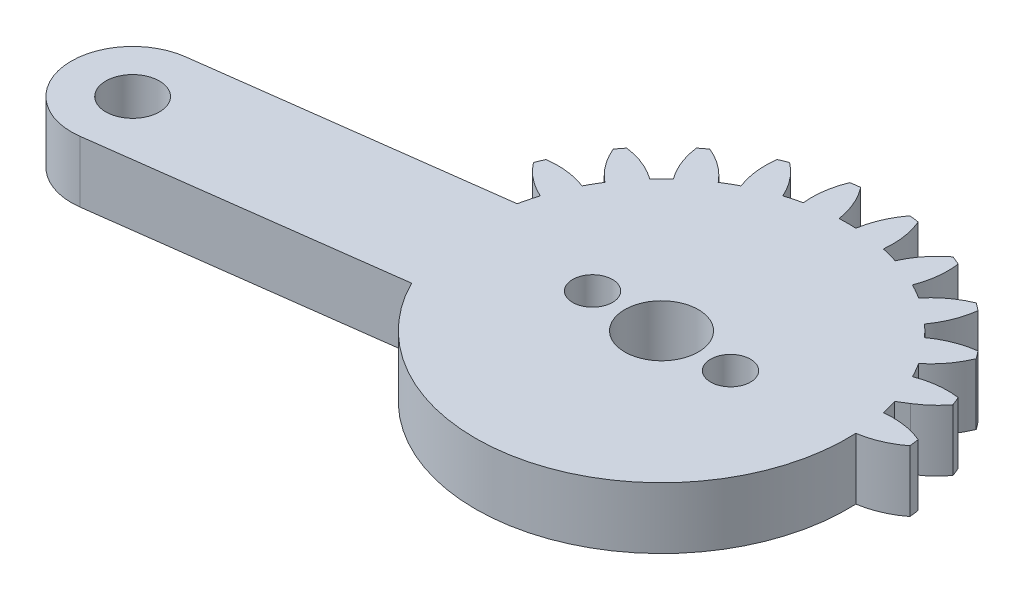
SolidWorks part; units mm, degrees
ref_plane "Front Plane" through (0, 0, 0) normal (0, 0, 1) x (1, 0, 0)
ref_plane "Top Plane" through (0, 0, 0) normal (0, 1, 0) x (1, 0, 0)
ref_plane "Right Plane" through (0, 0, 0) normal (1, 0, 0) x (0, 0, -1)
sketch "Sketch1" plane through (0, 0, 0) normal (0, 1, 0) x (1, 0, 0)
  line L0 (20.6437, 4) -> (2.0816, 4)
  line L1 (2.0816, -4) -> (20.6437, -4)
  arc A0 (2.0816, 4) -> (3.5217, 5.3071) centre (-0.7683, 8.5867) ccw
  arc A1 (3.5217, 5.3071) -> (3.2829, 5.8838) centre (-10.1063, 0) ccw
  arc A2 (3.2829, 5.8838) -> (0.6271, 5.5703) centre (2.5684, 0.5313) ccw
  arc A3 (0.6271, 5.5703) -> (0.0844, 6.5103) centre (-10.1063, 0) ccw
  arc A4 (0.0844, 6.5103) -> (1.6838, 8.6535) centre (-3.3089, 10.711) ccw
  arc A5 (1.6838, 8.6535) -> (1.3038, 9.1487) centre (-10.1063, 0) ccw
  arc A6 (1.3038, 9.1487) -> (-1.1803, 8.1585) centre (1.999, 3.7936) ccw
  arc A7 (-1.1803, 8.1585) -> (-1.9479, 8.926) centre (-10.1063, 0) ccw
  arc A8 (-1.9479, 8.926) -> (-0.9576, 11.4102) centre (-6.3127, 12.1053) ccw
  arc A9 (-0.9576, 11.4102) -> (-1.4528, 11.7901) centre (-10.1063, 0) ccw
  arc A10 (-1.4528, 11.7901) -> (-3.596, 10.1907) centre (0.6046, 6.7975) ccw
  arc A11 (-3.596, 10.1907) -> (-4.5361, 10.7334) centre (-10.1063, 0) ccw
  arc A12 (-4.5361, 10.7334) -> (-4.2225, 13.3892) centre (-9.5751, 12.6747) ccw
  arc A13 (-4.2225, 13.3892) -> (-4.7992, 13.6281) centre (-10.1063, 0) ccw
  arc A14 (-4.7992, 13.6281) -> (-6.4554, 11.5285) centre (-1.5196, 9.3381) ccw
  arc A15 (-6.4554, 11.5285) -> (-7.5039, 11.8094) centre (-10.1063, 0) ccw
  arc A16 (-7.5039, 11.8094) -> (-7.8884, 14.4558) centre (-12.8736, 12.3803) ccw
  arc A17 (-7.8884, 14.4558) -> (-8.5072, 14.5373) centre (-10.1063, 0) ccw
  arc A18 (-8.5072, 14.5373) -> (-9.5636, 12.0806) centre (-4.2291, 11.2423) ccw
  arc A19 (-9.5636, 12.0806) -> (-10.6491, 12.0806) centre (-10.1063, 0) ccw
  arc A20 (-10.6491, 12.0806) -> (-11.7054, 14.5373) centre (-15.9836, 11.2423) ccw
  arc A21 (-11.7054, 14.5373) -> (-12.3243, 14.4558) centre (-10.1063, 0) ccw
  arc A22 (-12.3243, 14.4558) -> (-12.7088, 11.8094) centre (-7.3391, 12.3803) ccw
  arc A23 (-12.7088, 11.8094) -> (-13.7573, 11.5285) centre (-10.1063, 0) ccw
  arc A24 (-13.7573, 11.5285) -> (-15.4135, 13.6281) centre (-18.6931, 9.3381) ccw
  arc A25 (-15.4135, 13.6281) -> (-15.9901, 13.3892) centre (-10.1063, 0) ccw
  arc A26 (-15.9901, 13.3892) -> (-15.6766, 10.7334) centre (-10.6376, 12.6747) ccw
  arc A27 (-15.6766, 10.7334) -> (-16.6166, 10.1907) centre (-10.1063, 0) ccw
  arc A28 (-16.6166, 10.1907) -> (-18.7599, 11.7901) centre (-20.8173, 6.7975) ccw
  arc A29 (-18.7599, 11.7901) -> (-19.255, 11.4102) centre (-10.1063, 0) ccw
  arc A30 (-19.255, 11.4102) -> (-18.2648, 8.926) centre (-13.9, 12.1053) ccw
  arc A31 (-18.2648, 8.926) -> (-19.0324, 8.1585) centre (-10.1063, 0) ccw
  arc A32 (-19.0324, 8.1585) -> (-21.5165, 9.1487) centre (-22.2117, 3.7936) ccw
  arc A33 (-21.5165, 9.1487) -> (-21.8965, 8.6535) centre (-10.1063, 0) ccw
  arc A34 (-21.8965, 8.6535) -> (-20.2971, 6.5103) centre (-16.9038, 10.711) ccw
  arc A35 (-20.2971, 6.5103) -> (-20.8398, 5.5703) centre (-10.1063, 0) ccw
  arc A36 (-20.8398, 5.5703) -> (-23.4956, 5.8838) centre (-22.7811, 0.5313) ccw
  arc A37 (-23.4956, 5.8838) -> (-23.7344, 5.3071) centre (-10.1063, 0) ccw
  arc A38 (-23.7344, 5.3071) -> (-21.6348, 3.6509) centre (-19.4444, 8.5867) ccw
  arc A39 (-21.6348, 3.6509) -> (-21.9157, 2.6025) centre (-10.1063, 0) ccw
  arc A40 (-21.9157, 2.6025) -> (-24.5622, 2.2179) centre (-22.4867, -2.7673) ccw
  arc A41 (-24.5622, 2.2179) -> (-24.6437, 1.5991) centre (-10.1063, 0) ccw
  arc A42 (-24.6437, 1.5991) -> (-22.1869, 0.5427) centre (-21.3486, 5.8773) ccw
  arc A43 (-22.1869, 0.5427) -> (-22.1869, -0.5427) centre (-10.1063, 0) ccw
  arc A44 (-22.1869, -0.5427) -> (-24.6437, -1.5991) centre (-21.3486, -5.8773) ccw
  arc A45 (-24.6437, -1.5991) -> (-24.5622, -2.2179) centre (-10.1063, 0) ccw
  arc A46 (-24.5622, -2.2179) -> (-21.9157, -2.6025) centre (-22.4867, 2.7673) ccw
  arc A47 (-21.9157, -2.6025) -> (-21.6348, -3.6509) centre (-10.1063, 0) ccw
  arc A48 (-21.6348, -3.6509) -> (-23.7344, -5.3071) centre (-19.4444, -8.5867) ccw
  arc A49 (-23.7344, -5.3071) -> (-23.4956, -5.8838) centre (-10.1063, 0) ccw
  arc A50 (-23.4956, -5.8838) -> (-20.8398, -5.5703) centre (-22.7811, -0.5313) ccw
  arc A51 (-20.8398, -5.5703) -> (-20.2971, -6.5103) centre (-10.1063, 0) ccw
  arc A52 (-20.2971, -6.5103) -> (-21.8965, -8.6535) centre (-16.9038, -10.711) ccw
  arc A53 (-21.8965, -8.6535) -> (-21.5165, -9.1487) centre (-10.1063, 0) ccw
  arc A54 (-21.5165, -9.1487) -> (-19.0324, -8.1585) centre (-22.2117, -3.7936) ccw
  arc A55 (-19.0324, -8.1585) -> (-18.2648, -8.926) centre (-10.1063, 0) ccw
  arc A56 (-18.2648, -8.926) -> (-19.255, -11.4102) centre (-13.9, -12.1053) ccw
  arc A57 (-19.255, -11.4102) -> (-18.7599, -11.7901) centre (-10.1063, 0) ccw
  arc A58 (-18.7599, -11.7901) -> (-16.6166, -10.1907) centre (-20.8173, -6.7975) ccw
  arc A59 (-16.6166, -10.1907) -> (-15.6766, -10.7334) centre (-10.1063, 0) ccw
  arc A60 (-15.6766, -10.7334) -> (-15.9901, -13.3892) centre (-10.6376, -12.6747) ccw
  arc A61 (-15.9901, -13.3892) -> (-15.4135, -13.6281) centre (-10.1063, 0) ccw
  arc A62 (-15.4135, -13.6281) -> (-13.7573, -11.5285) centre (-18.6931, -9.3381) ccw
  arc A63 (-13.7573, -11.5285) -> (-12.7088, -11.8094) centre (-10.1063, 0) ccw
  arc A64 (-12.7088, -11.8094) -> (-12.3243, -14.4558) centre (-7.3391, -12.3803) ccw
  arc A65 (-12.3243, -14.4558) -> (-11.7054, -14.5373) centre (-10.1063, 0) ccw
  arc A66 (-11.7054, -14.5373) -> (-10.6491, -12.0806) centre (-15.9836, -11.2423) ccw
  arc A67 (-10.6491, -12.0806) -> (-9.5636, -12.0806) centre (-10.1063, 0) ccw
  arc A68 (-9.5636, -12.0806) -> (-8.5072, -14.5373) centre (-4.2291, -11.2423) ccw
  arc A69 (-8.5072, -14.5373) -> (-7.8884, -14.4558) centre (-10.1063, 0) ccw
  arc A70 (-7.8884, -14.4558) -> (-7.5039, -11.8094) centre (-12.8736, -12.3803) ccw
  arc A71 (-7.5039, -11.8094) -> (-6.4554, -11.5285) centre (-10.1063, 0) ccw
  arc A72 (-6.4554, -11.5285) -> (-4.7992, -13.6281) centre (-1.5196, -9.3381) ccw
  arc A73 (-4.7992, -13.6281) -> (-4.2225, -13.3892) centre (-10.1063, 0) ccw
  arc A74 (-4.2225, -13.3892) -> (-4.5361, -10.7334) centre (-9.5751, -12.6747) ccw
  arc A75 (-4.5361, -10.7334) -> (-3.596, -10.1907) centre (-10.1063, 0) ccw
  arc A76 (-3.596, -10.1907) -> (-1.4528, -11.7901) centre (0.6046, -6.7975) ccw
  arc A77 (-1.4528, -11.7901) -> (-0.9576, -11.4102) centre (-10.1063, 0) ccw
  arc A78 (-0.9576, -11.4102) -> (-1.9479, -8.926) centre (-6.3127, -12.1053) ccw
  arc A79 (-1.9479, -8.926) -> (-1.1803, -8.1585) centre (-10.1063, 0) ccw
  arc A80 (-1.1803, -8.1585) -> (1.3038, -9.1487) centre (1.999, -3.7936) ccw
  arc A81 (1.3038, -9.1487) -> (1.6838, -8.6535) centre (-10.1063, 0) ccw
  arc A82 (1.6838, -8.6535) -> (0.0844, -6.5103) centre (-3.3089, -10.711) ccw
  arc A83 (0.0844, -6.5103) -> (0.6271, -5.5703) centre (-10.1063, 0) ccw
  arc A84 (0.6271, -5.5703) -> (3.2829, -5.8838) centre (2.5684, -0.5313) ccw
  arc A85 (3.2829, -5.8838) -> (3.5217, -5.3071) centre (-10.1063, 0) ccw
  arc A86 (3.5217, -5.3071) -> (2.0816, -4) centre (-0.7683, -8.5867) ccw
  arc A87 (20.6437, -4) -> (20.6437, 4) centre (20.6437, 0) ccw
  circle A88 centre (-10.1063, 0) radius 1.5
  circle A89 centre (20.6437, 0) radius 1.5
  dimension "D1" = 3
  dimension "D2" = 3
extrude "Boss-Extrude1" add sketch "Sketch1" along normal blind 4
scale "Scale1" scale about centroid uniform scaling yes scale factor 1.004
sketch "Sketch3" plane through (0, 4.008, 0) normal (0, 1, 0) x (1, 0, 0)
  line L0 (-10.1272, 0) -> (-40.8563, 0) construction
  line L1 (-10.1272, 0) -> (-40.6142, -4.0137)
  line L2 (-10.6494, 3.9658) -> (-41.1363, -0.0479)
  line L3 (-9.6051, -3.9658) -> (-40.0921, -7.9795)
  line L4 (-10.1272, 0) -> (-4.5081, 13.5658) construction
  line L5 (-10.1272, 0) -> (-8.2107, 14.5579) construction
  circle A0 centre (-10.1272, 0) radius 1.5
  circle A1 centre (20.7458, 0) radius 1.506 construction
  circle A2 centre (20.7458, 0) radius 1.506
  circle A3 centre (-40.6142, -4.0137) radius 1.75
  circle A4 centre (-40.6142, -4.0137) radius 4
  circle A5 centre (-10.1272, 0) radius 4
  arc A6 (-4.2199, 13.4428) -> (-4.7989, 13.6826) centre (-10.1272, 0) ccw construction
  arc A7 (-7.9004, 14.5137) -> (-8.5218, 14.5955) centre (-10.1272, 0) ccw construction
  dimension "D2" = 3
  dimension "D5" = 3.5
  dimension "D6" = 8
  dimension "D7" = 8
  dimension "D1" = 30.75
  dimension "D4" = 7.5
extrude "Boss-Extrude2" add sketch "Sketch3" against normal blind 4
sketch "Sketch4" plane through (0, 4.008, 0) normal (0, 1, 0) x (1, 0, 0)
  line L0 (20.7458, 4.016) -> (2.1095, 4.016) construction
  line L1 (2.1095, -4.016) -> (20.7458, -4.016) construction
  line L2 (20.7458, 4.016) -> (2.1095, 4.016)
  line L3 (2.1095, -4.016) -> (20.7458, -4.016)
  line L4 (2.1095, 4.016) -> (1.4634, 3.6145)
  line L5 (-21.6248, -5.5482) -> (-20.9704, -5.462)
  line L6 (-10.1272, 0) -> (0.1042, 6.5363) construction
  line L7 (-10.1272, 0) -> (2.0016, 0.5449) construction
  line L8 (-24.6567, 2.1217) -> (-41.1363, -0.0479)
  line L9 (-40.0921, -7.9795) -> (-23.6124, -5.8099)
  line L10 (2.1095, -4.016) -> (20.7458, -4.016)
  line L11 (20.7458, 4.016) -> (2.1095, 4.016)
  line L12 (-22.0146, 2.4695) -> (-41.1363, -0.0479)
  line L13 (-40.0921, -7.9795) -> (-21.6248, -5.5482)
  line L14 (2.1095, -4.016) -> (20.7458, -4.016)
  line L15 (20.7458, 4.016) -> (2.1095, 4.016)
  circle A0 centre (-10.1272, 0) radius 12.1411
  arc A1 (3.3155, 5.9073) -> (0.6491, 5.5926) centre (2.5982, 0.5334) ccw construction
  arc A2 (3.5554, 5.3284) -> (3.3155, 5.9073) centre (-10.1272, 0) ccw construction
  arc A3 (2.1095, 4.016) -> (3.5554, 5.3284) centre (-0.7518, 8.6211) ccw construction
  arc A4 (20.7458, -4.016) -> (20.7458, 4.016) centre (20.7458, 0) ccw construction
  arc A5 (3.5554, -5.3284) -> (2.1095, -4.016) centre (-0.7518, -8.6211) ccw construction
  arc A6 (3.3155, -5.9073) -> (3.5554, -5.3284) centre (-10.1272, 0) ccw construction
  arc A7 (0.6491, -5.5926) -> (3.3155, -5.9073) centre (2.5982, -0.5334) ccw construction
  arc A8 (3.3155, 5.9073) -> (0.6491, 5.5926) centre (2.5982, 0.5334) ccw
  arc A9 (3.5554, 5.3284) -> (3.3155, 5.9073) centre (-10.1272, 0) ccw
  arc A10 (2.1095, 4.016) -> (3.5554, 5.3284) centre (-0.7518, 8.6211) ccw
  arc A11 (20.7458, -4.016) -> (20.7458, 4.016) centre (20.7458, 0) ccw
  arc A12 (3.5554, -5.3284) -> (2.1095, -4.016) centre (-0.7518, -8.6211) ccw
  arc A13 (3.3155, -5.9073) -> (3.5554, -5.3284) centre (-10.1272, 0) ccw
  arc A14 (0.6491, -5.5926) -> (3.3155, -5.9073) centre (2.5982, -0.5334) ccw
  arc A15 (2.0016, 0.5449) -> (4.4682, 1.6055) centre (1.16, 5.9008) ccw
  arc A16 (4.3864, 2.2268) -> (1.7294, 2.6129) centre (2.3026, -2.7783) ccw
  arc A17 (4.4682, 1.6055) -> (4.3864, 2.2268) centre (-10.1272, 0) ccw
  arc A95 (-21.7018, 3.6655) -> (-21.9839, 2.6129) centre (-10.1272, 0) ccw
  arc A96 (-41.1363, -0.0479) -> (-40.0921, -7.9795) centre (-40.6142, -4.0137) ccw
  arc A97 (-20.3587, -6.5363) -> (-21.9645, -8.6881) centre (-16.9519, -10.7538) ccw
  arc A98 (-21.9645, -8.6881) -> (-21.5831, -9.1853) centre (-10.1272, 0) ccw
  arc A99 (-21.5831, -9.1853) -> (-19.089, -8.1911) centre (-22.281, -3.8088) ccw
  arc A100 (-19.089, -8.1911) -> (-18.3184, -8.9617) centre (-10.1272, 0) ccw
  arc A101 (-18.3184, -8.9617) -> (-19.3125, -11.4558) centre (-13.9361, -12.1538) ccw
  arc A102 (-19.3125, -11.4558) -> (-18.8154, -11.8373) centre (-10.1272, 0) ccw
  arc A103 (-18.8154, -11.8373) -> (-16.6636, -10.2315) centre (-20.8811, -6.8247) ccw
  arc A104 (-16.6636, -10.2315) -> (-15.7198, -10.7764) centre (-10.1272, 0) ccw
  arc A105 (-15.7198, -10.7764) -> (-16.0346, -13.4428) centre (-10.6607, -12.7254) ccw
  arc A106 (-16.0346, -13.4428) -> (-15.4556, -13.6826) centre (-10.1272, 0) ccw
  arc A107 (-15.4556, -13.6826) -> (-13.7928, -11.5746) centre (-18.7483, -9.3754) ccw
  arc A108 (-13.7928, -11.5746) -> (-12.7401, -11.8566) centre (-10.1272, 0) ccw
  arc A109 (-12.7401, -11.8566) -> (-12.354, -14.5137) centre (-7.3489, -12.4299) ccw
  arc A110 (-12.354, -14.5137) -> (-11.7327, -14.5955) centre (-10.1272, 0) ccw
  arc A111 (-11.7327, -14.5955) -> (-10.6721, -12.1289) centre (-16.028, -11.2872) ccw
  arc A112 (-10.6721, -12.1289) -> (-9.5824, -12.1289) centre (-10.1272, 0) ccw
  arc A113 (-9.5824, -12.1289) -> (-8.5218, -14.5955) centre (-4.2265, -11.2872) ccw
  arc A114 (-8.5218, -14.5955) -> (-7.9004, -14.5137) centre (-10.1272, 0) ccw
  arc A115 (-7.9004, -14.5137) -> (-7.5144, -11.8566) centre (-12.9056, -12.4299) ccw
  arc A116 (-7.5144, -11.8566) -> (-6.4617, -11.5746) centre (-10.1272, 0) ccw
  arc A117 (-6.4617, -11.5746) -> (-4.7989, -13.6826) centre (-1.5062, -9.3754) ccw
  arc A118 (-4.7989, -13.6826) -> (-4.2199, -13.4428) centre (-10.1272, 0) ccw
  arc A119 (-4.2199, -13.4428) -> (-4.5347, -10.7764) centre (-9.5938, -12.7254) ccw
  arc A120 (-4.5347, -10.7764) -> (-3.5909, -10.2315) centre (-10.1272, 0) ccw
  arc A121 (-3.5909, -10.2315) -> (-1.4391, -11.8373) centre (0.6266, -6.8247) ccw
  arc A122 (-1.4391, -11.8373) -> (-0.942, -11.4558) centre (-10.1272, 0) ccw
  arc A123 (-0.942, -11.4558) -> (-1.9361, -8.9617) centre (-6.3184, -12.1538) ccw
  arc A124 (-1.9361, -8.9617) -> (-1.1655, -8.1911) centre (-10.1272, 0) ccw
  arc A125 (-1.1655, -8.1911) -> (1.3286, -9.1853) centre (2.0265, -3.8088) ccw
  arc A126 (1.3286, -9.1853) -> (1.71, -8.6881) centre (-10.1272, 0) ccw
  arc A127 (1.71, -8.6881) -> (0.1042, -6.5363) centre (-3.3026, -10.7538) ccw
  arc A128 (0.1042, -6.5363) -> (0.6491, -5.5926) centre (-10.1272, 0) ccw
  arc A129 (0.6491, -5.5926) -> (3.3155, -5.9073) centre (2.5982, -0.5334) ccw
  arc A130 (3.3155, -5.9073) -> (3.5554, -5.3284) centre (-10.1272, 0) ccw
  arc A131 (3.5554, -5.3284) -> (2.1095, -4.016) centre (-0.7518, -8.6211) ccw
  arc A132 (20.7458, -4.016) -> (20.7458, 4.016) centre (20.7458, 0) ccw
  arc A133 (2.1095, 4.016) -> (3.5554, 5.3284) centre (-0.7518, 8.6211) ccw
  arc A134 (3.5554, 5.3284) -> (3.3155, 5.9073) centre (-10.1272, 0) ccw
  arc A135 (3.3155, 5.9073) -> (0.6491, 5.5926) centre (2.5982, 0.5334) ccw
  arc A136 (0.6491, 5.5926) -> (0.1042, 6.5363) centre (-10.1272, 0) ccw
  arc A137 (0.1042, 6.5363) -> (1.71, 8.6881) centre (-3.3026, 10.7538) ccw
  arc A138 (1.71, 8.6881) -> (1.3286, 9.1853) centre (-10.1272, 0) ccw
  arc A139 (1.3286, 9.1853) -> (-1.1655, 8.1911) centre (2.0265, 3.8088) ccw
  arc A140 (-1.1655, 8.1911) -> (-1.9361, 8.9617) centre (-10.1272, 0) ccw
  arc A141 (-1.9361, 8.9617) -> (-0.942, 11.4558) centre (-6.3184, 12.1538) ccw
  arc A142 (-0.942, 11.4558) -> (-1.4391, 11.8373) centre (-10.1272, 0) ccw
  arc A143 (-1.4391, 11.8373) -> (-3.5909, 10.2315) centre (0.6266, 6.8247) ccw
  arc A144 (-3.5909, 10.2315) -> (-4.5347, 10.7764) centre (-10.1272, 0) ccw
  arc A145 (-4.5347, 10.7764) -> (-4.2199, 13.4428) centre (-9.5938, 12.7254) ccw
  arc A146 (-4.2199, 13.4428) -> (-4.7989, 13.6826) centre (-10.1272, 0) ccw
  arc A147 (-4.7989, 13.6826) -> (-6.4617, 11.5746) centre (-1.5062, 9.3754) ccw
  arc A148 (-6.4617, 11.5746) -> (-7.5144, 11.8566) centre (-10.1272, 0) ccw
  arc A149 (-7.5144, 11.8566) -> (-7.9004, 14.5137) centre (-12.9056, 12.4299) ccw
  arc A150 (-7.9004, 14.5137) -> (-8.5218, 14.5955) centre (-10.1272, 0) ccw
  arc A151 (-8.5218, 14.5955) -> (-9.5824, 12.1289) centre (-4.2265, 11.2872) ccw
  arc A152 (-9.5824, 12.1289) -> (-10.6721, 12.1289) centre (-10.1272, 0) ccw
  arc A153 (-10.6721, 12.1289) -> (-11.7327, 14.5955) centre (-16.028, 11.2872) ccw
  arc A154 (-11.7327, 14.5955) -> (-12.354, 14.5137) centre (-10.1272, 0) ccw
  arc A155 (-12.354, 14.5137) -> (-12.7401, 11.8566) centre (-7.3489, 12.4299) ccw
  arc A156 (-12.7401, 11.8566) -> (-13.7928, 11.5746) centre (-10.1272, 0) ccw
  arc A157 (-13.7928, 11.5746) -> (-15.4556, 13.6826) centre (-18.7483, 9.3754) ccw
  arc A158 (-15.4556, 13.6826) -> (-16.0346, 13.4428) centre (-10.1272, 0) ccw
  arc A159 (-16.0346, 13.4428) -> (-15.7198, 10.7764) centre (-10.6607, 12.7254) ccw
  arc A160 (-15.7198, 10.7764) -> (-16.6636, 10.2315) centre (-10.1272, 0) ccw
  arc A161 (-16.6636, 10.2315) -> (-18.8154, 11.8373) centre (-20.8811, 6.8247) ccw
  arc A162 (-18.8154, 11.8373) -> (-19.3125, 11.4558) centre (-10.1272, 0) ccw
  arc A163 (-19.3125, 11.4558) -> (-18.3184, 8.9617) centre (-13.9361, 12.1538) ccw
  arc A164 (-18.3184, 8.9617) -> (-19.089, 8.1911) centre (-10.1272, 0) ccw
  arc A165 (-19.089, 8.1911) -> (-21.5831, 9.1853) centre (-22.281, 3.8088) ccw
  arc A166 (-21.5831, 9.1853) -> (-21.9645, 8.6881) centre (-10.1272, 0) ccw
  arc A167 (-21.9645, 8.6881) -> (-20.3587, 6.5363) centre (-16.9519, 10.7538) ccw
  arc A168 (-20.3587, 6.5363) -> (-20.9036, 5.5926) centre (-10.1272, 0) ccw
  arc A169 (-20.9036, 5.5926) -> (-23.57, 5.9073) centre (-22.8527, 0.5334) ccw
  arc A170 (-23.57, 5.9073) -> (-23.8099, 5.3284) centre (-10.1272, 0) ccw
  arc A171 (-23.8099, 5.3284) -> (-21.7018, 3.6655) centre (-19.5027, 8.6211) ccw
  arc A172 (-21.7018, 3.6655) -> (-21.9839, 2.6129) centre (-10.1272, 0) ccw
  arc A175 (-23.57, -5.9073) -> (-20.9036, -5.5926) centre (-22.8527, -0.5334) ccw
  arc A176 (-41.1363, -0.0479) -> (-40.0921, -7.9795) centre (-40.6142, -4.0137) ccw
  arc A177 (-20.3587, -6.5363) -> (-21.9645, -8.6881) centre (-16.9519, -10.7538) ccw
  arc A178 (-21.9645, -8.6881) -> (-21.5831, -9.1853) centre (-10.1272, 0) ccw
  arc A179 (-21.5831, -9.1853) -> (-19.089, -8.1911) centre (-22.281, -3.8088) ccw
  arc A180 (-19.089, -8.1911) -> (-18.3184, -8.9617) centre (-10.1272, 0) ccw
  arc A181 (-18.3184, -8.9617) -> (-19.3125, -11.4558) centre (-13.9361, -12.1538) ccw
  arc A182 (-19.3125, -11.4558) -> (-18.8154, -11.8373) centre (-10.1272, 0) ccw
  arc A183 (-18.8154, -11.8373) -> (-16.6636, -10.2315) centre (-20.8811, -6.8247) ccw
  arc A184 (-16.6636, -10.2315) -> (-15.7198, -10.7764) centre (-10.1272, 0) ccw
  arc A185 (-15.7198, -10.7764) -> (-16.0346, -13.4428) centre (-10.6607, -12.7254) ccw
  arc A186 (-16.0346, -13.4428) -> (-15.4556, -13.6826) centre (-10.1272, 0) ccw
  arc A187 (-15.4556, -13.6826) -> (-13.7928, -11.5746) centre (-18.7483, -9.3754) ccw
  arc A188 (-13.7928, -11.5746) -> (-12.7401, -11.8566) centre (-10.1272, 0) ccw
  arc A189 (-12.7401, -11.8566) -> (-12.354, -14.5137) centre (-7.3489, -12.4299) ccw
  arc A190 (-12.354, -14.5137) -> (-11.7327, -14.5955) centre (-10.1272, 0) ccw
  arc A191 (-11.7327, -14.5955) -> (-10.6721, -12.1289) centre (-16.028, -11.2872) ccw
  arc A192 (-10.6721, -12.1289) -> (-9.5824, -12.1289) centre (-10.1272, 0) ccw
  arc A193 (-9.5824, -12.1289) -> (-8.5218, -14.5955) centre (-4.2265, -11.2872) ccw
  arc A194 (-8.5218, -14.5955) -> (-7.9004, -14.5137) centre (-10.1272, 0) ccw
  arc A195 (-7.9004, -14.5137) -> (-7.5144, -11.8566) centre (-12.9056, -12.4299) ccw
  arc A196 (-7.5144, -11.8566) -> (-6.4617, -11.5746) centre (-10.1272, 0) ccw
  arc A197 (-6.4617, -11.5746) -> (-4.7989, -13.6826) centre (-1.5062, -9.3754) ccw
  arc A198 (-4.7989, -13.6826) -> (-4.2199, -13.4428) centre (-10.1272, 0) ccw
  arc A199 (-4.2199, -13.4428) -> (-4.5347, -10.7764) centre (-9.5938, -12.7254) ccw
  arc A200 (-4.5347, -10.7764) -> (-3.5909, -10.2315) centre (-10.1272, 0) ccw
  arc A201 (-3.5909, -10.2315) -> (-1.4391, -11.8373) centre (0.6266, -6.8247) ccw
  arc A202 (-1.4391, -11.8373) -> (-0.942, -11.4558) centre (-10.1272, 0) ccw
  arc A203 (-0.942, -11.4558) -> (-1.9361, -8.9617) centre (-6.3184, -12.1538) ccw
  arc A204 (-1.9361, -8.9617) -> (-1.1655, -8.1911) centre (-10.1272, 0) ccw
  arc A205 (-1.1655, -8.1911) -> (1.3286, -9.1853) centre (2.0265, -3.8088) ccw
  arc A206 (1.3286, -9.1853) -> (1.71, -8.6881) centre (-10.1272, 0) ccw
  arc A207 (1.71, -8.6881) -> (0.1042, -6.5363) centre (-3.3026, -10.7538) ccw
  arc A208 (0.1042, -6.5363) -> (0.6491, -5.5926) centre (-10.1272, 0) ccw
  arc A209 (0.6491, -5.5926) -> (3.3155, -5.9073) centre (2.5982, -0.5334) ccw
  arc A210 (3.3155, -5.9073) -> (3.5554, -5.3284) centre (-10.1272, 0) ccw
  arc A211 (3.5554, -5.3284) -> (2.1095, -4.016) centre (-0.7518, -8.6211) ccw
  arc A212 (20.7458, -4.016) -> (20.7458, 4.016) centre (20.7458, 0) ccw
  arc A213 (2.1095, 4.016) -> (3.5554, 5.3284) centre (-0.7518, 8.6211) ccw
  arc A214 (3.5554, 5.3284) -> (3.3155, 5.9073) centre (-10.1272, 0) ccw
  arc A215 (3.3155, 5.9073) -> (0.6491, 5.5926) centre (2.5982, 0.5334) ccw
  arc A216 (0.6491, 5.5926) -> (0.1042, 6.5363) centre (-10.1272, 0) ccw
  arc A217 (0.1042, 6.5363) -> (1.71, 8.6881) centre (-3.3026, 10.7538) ccw
  arc A218 (1.71, 8.6881) -> (1.3286, 9.1853) centre (-10.1272, 0) ccw
  arc A219 (1.3286, 9.1853) -> (-1.1655, 8.1911) centre (2.0265, 3.8088) ccw
  arc A220 (-1.1655, 8.1911) -> (-1.9361, 8.9617) centre (-10.1272, 0) ccw
  arc A221 (-1.9361, 8.9617) -> (-0.942, 11.4558) centre (-6.3184, 12.1538) ccw
  arc A222 (-0.942, 11.4558) -> (-1.4391, 11.8373) centre (-10.1272, 0) ccw
  arc A223 (-1.4391, 11.8373) -> (-3.5909, 10.2315) centre (0.6266, 6.8247) ccw
  arc A224 (-3.5909, 10.2315) -> (-4.5347, 10.7764) centre (-10.1272, 0) ccw
  arc A225 (-4.5347, 10.7764) -> (-4.2199, 13.4428) centre (-9.5938, 12.7254) ccw
  arc A226 (-4.2199, 13.4428) -> (-4.7989, 13.6826) centre (-10.1272, 0) ccw
  arc A227 (-4.7989, 13.6826) -> (-6.4617, 11.5746) centre (-1.5062, 9.3754) ccw
  arc A228 (-6.4617, 11.5746) -> (-7.5144, 11.8566) centre (-10.1272, 0) ccw
  arc A229 (-7.5144, 11.8566) -> (-7.9004, 14.5137) centre (-12.9056, 12.4299) ccw
  arc A230 (-7.9004, 14.5137) -> (-8.5218, 14.5955) centre (-10.1272, 0) ccw
  arc A231 (-8.5218, 14.5955) -> (-9.5824, 12.1289) centre (-4.2265, 11.2872) ccw
  arc A232 (-9.5824, 12.1289) -> (-10.6721, 12.1289) centre (-10.1272, 0) ccw
  arc A233 (-10.6721, 12.1289) -> (-11.7327, 14.5955) centre (-16.028, 11.2872) ccw
  arc A234 (-11.7327, 14.5955) -> (-12.354, 14.5137) centre (-10.1272, 0) ccw
  arc A235 (-12.354, 14.5137) -> (-12.7401, 11.8566) centre (-7.3489, 12.4299) ccw
  arc A236 (-12.7401, 11.8566) -> (-13.7928, 11.5746) centre (-10.1272, 0) ccw
  arc A237 (-13.7928, 11.5746) -> (-15.4556, 13.6826) centre (-18.7483, 9.3754) ccw
  arc A238 (-15.4556, 13.6826) -> (-16.0346, 13.4428) centre (-10.1272, 0) ccw
  arc A239 (-16.0346, 13.4428) -> (-15.7198, 10.7764) centre (-10.6607, 12.7254) ccw
  arc A240 (-15.7198, 10.7764) -> (-16.6636, 10.2315) centre (-10.1272, 0) ccw
  arc A241 (-16.6636, 10.2315) -> (-18.8154, 11.8373) centre (-20.8811, 6.8247) ccw
  arc A242 (-18.8154, 11.8373) -> (-19.3125, 11.4558) centre (-10.1272, 0) ccw
  arc A243 (-19.3125, 11.4558) -> (-18.3184, 8.9617) centre (-13.9361, 12.1538) ccw
  arc A244 (-18.3184, 8.9617) -> (-19.089, 8.1911) centre (-10.1272, 0) ccw
  arc A245 (-19.089, 8.1911) -> (-21.5831, 9.1853) centre (-22.281, 3.8088) ccw
  arc A246 (-21.5831, 9.1853) -> (-21.9645, 8.6881) centre (-10.1272, 0) ccw
  arc A247 (-21.9645, 8.6881) -> (-20.3587, 6.5363) centre (-16.9519, 10.7538) ccw
  arc A248 (-20.3587, 6.5363) -> (-20.9036, 5.5926) centre (-10.1272, 0) ccw
  arc A249 (-20.9036, 5.5926) -> (-23.57, 5.9073) centre (-22.8527, 0.5334) ccw
  arc A250 (-23.57, 5.9073) -> (-23.8099, 5.3284) centre (-10.1272, 0) ccw
  arc A251 (-23.8099, 5.3284) -> (-21.7018, 3.6655) centre (-19.5027, 8.6211) ccw
  arc A252 (-23.57, -5.9073) -> (-20.9036, -5.5926) centre (-22.8527, -0.5334) ccw
  arc A253 (-20.9036, -5.5926) -> (-20.3587, -6.5363) centre (-10.1272, 0) ccw
  arc A254 (-20.9036, -5.5926) -> (-20.3587, -6.5363) centre (-10.1272, 0) ccw
  arc A255 (-23.6124, -5.8099) -> (-23.57, -5.9073) centre (-10.1272, 0) ccw
  arc A256 (-23.6124, -5.8099) -> (-23.57, -5.9073) centre (-10.1272, 0) ccw
  arc A257 (-21.9839, 2.6129) -> (-24.6409, 2.2268) centre (-22.5571, -2.7783) ccw
  arc A258 (-21.9839, 2.6129) -> (-24.6409, 2.2268) centre (-22.5571, -2.7783) ccw
  arc A259 (-24.6409, 2.2268) -> (-24.6567, 2.1217) centre (-10.1272, 0) ccw
  arc A260 (-24.6409, 2.2268) -> (-24.6567, 2.1217) centre (-10.1272, 0) ccw
  point P40 (-10.1272, 0)
  dimension "D2" = 24.2822
  dimension "D4" = 30
  dimension "D1" = 0
  dimension "D3" = 2
extrude "Cut-Extrude1" cut sketch "Sketch4" against normal up to surface (4.016 mm away) contours A178 A179 A0 L5 A177 | A182 A183 A0 A181 | A186 A187 A0 A185 | A190 A191 A0 A189 | A194 A195 A0 A193 | A198 A199 A0 A197 | A202 A203 A0 A201 | A206 A207 A0 A205 | A258 A260 L12 A0 | L13 A256 A252 A0 L5 | A0 A14 A13 A12 L3 A11 L2 L4
sketch "Sketch5" plane through (0, 4.008, 0) normal (0, 1, 0) x (1, 0, 0)
  circle A0 centre (-10.1272, 0) radius 2.4
  circle A1 centre (-5.6272, 0) radius 1.3
  circle A2 centre (-14.6272, 0) radius 1.3
  circle A3 centre (-10.1272, 0) radius 1.506 construction
  dimension "D1" = 4.8
  dimension "D2" = 2.6
  dimension "D3" = 2.6
  dimension "D4" = 4.5
  dimension "D5" = 9
extrude "Cut-Extrude2" cut sketch "Sketch5" against normal up to next contours A2 | A1 | A0
sketch "Sketch6" plane through (0, -0.008, 0) normal (0, -1, 0) x (1, 0, 0)
  line L1 (7.5773, -16.5725) -> (-27.0985, -16.5725)
  line L2 (7.5773, -16.5725) -> (7.5773, 13.8716)
  line L3 (7.5773, 13.8716) -> (-27.0985, 13.8716)
  line L4 (-27.0985, -16.5725) -> (-27.0985, 13.8716)
extrude "Cut-Extrude3" cut sketch "Sketch6" against normal up to surface (0.016 mm away) up to face at (-40.6142, 0.008, 5.7637)
